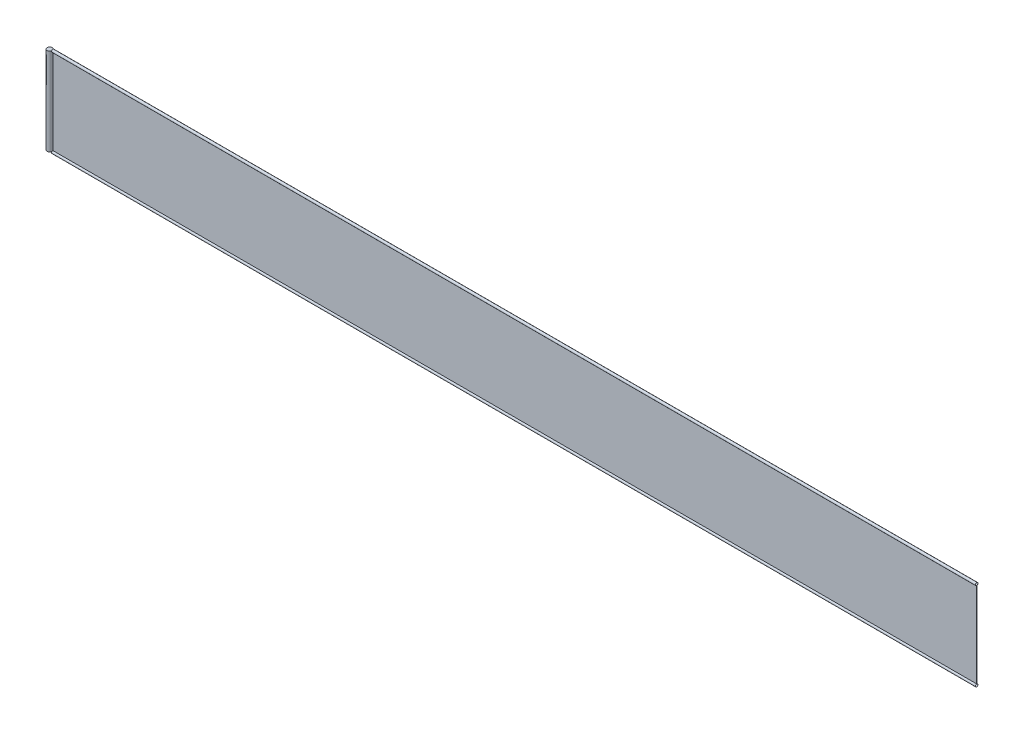
SolidWorks part; units mm, degrees
ref_plane "Front Plane" through (0, 0, 0) normal (0, 0, 1) x (1, 0, 0)
ref_plane "Top Plane" through (0, 0, 0) normal (0, 1, 0) x (1, 0, 0)
ref_plane "Right Plane" through (0, 0, 0) normal (1, 0, 0) x (0, 0, -1)
sketch "Sketch1" plane through (0, 0, 0) normal (0, 1, 0) x (1, 0, 0)
  circle A0 centre (1299.2899, 0) radius 120
extrude "Boss-Extrude1" add sketch "Sketch1" along normal blind 4100 from offset 2050
sketch "Sketch2" plane through (0, 0, 0) normal (0, 0, 1) x (1, 0, 0)
  line L1 (1449.2899, -2000) -> (44825.1381, -2000)
  line L2 (1449.2899, -2000) -> (1449.2899, 2000)
  line L3 (1449.2899, 2000) -> (44825.1381, 2000)
  line L4 (44825.1381, -2000) -> (44825.1381, 2000)
extrude "Boss-Extrude2" add sketch "Sketch2" along normal blind 3 from offset 1.5
sketch "Sketch3" plane through (0, 0, 0) normal (1, 0, 0) x (0, 0, -1)
  circle A0 centre (0, -2060) radius 60
  circle A1 centre (0, -2060) radius 57
extrude "Boss-Extrude3" add sketch "Sketch3" along normal blind 43375.8482 from offset 1449.2899
sketch "Sketch4" plane through (0, 0, 0) normal (1, 0, 0) x (0, 0, -1)
  circle A0 centre (0, 2060) radius 60
  circle A1 centre (0, 2060) radius 57
extrude "Boss-Extrude4" add sketch "Sketch4" along normal blind 43375.8482 from offset 1449.2899
